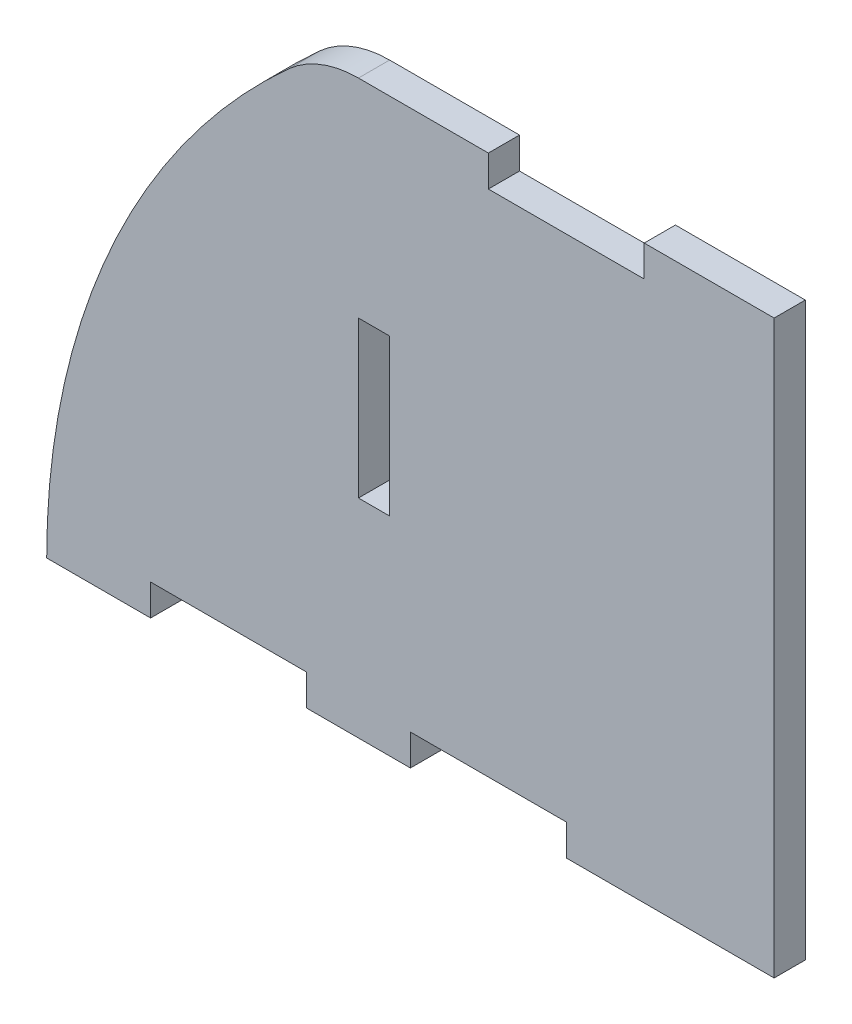
SolidWorks part; units mm, degrees
material "ABS PC"
ref_plane "Front Plane" through (0, 0, 0) normal (0, 0, 1) x (1, 0, 0)
ref_plane "Top Plane" through (0, 0, 0) normal (0, 1, 0) x (1, 0, 0)
ref_plane "Right Plane" through (0, 0, 0) normal (1, 0, 0) x (0, 0, -1)
sketch "Sketch1" plane through (0, 0, 0) normal (0, 0, 1) x (1, 0, 0)
  line L0 (0, 0) -> (0, 55)
  line L1 (0, 55) -> (-40, 55)
  line L2 (-40, 55) -> (-70, 55) construction
  line L3 (-70, 55) -> (-70, 0) construction
  line L4 (-70, 0) -> (0, 0)
  arc A0 (-46.701, 52.4227) -> (-70, 0) centre (0.625, 0) ccw
  arc A1 (-40, 55) -> (-46.701, 52.4227) centre (-40, 45) ccw
  dimension "D4" = 10
  dimension "D1" = 55
  dimension "D2" = 40
  dimension "D3" = 70
extrude "Boss-Extrude1" add sketch "Sketch1" along normal blind 3
sketch "Sketch2" plane through (0, 0, 3) normal (0, 0, 1) x (1, 0, 0)
  line L0 (0, 55) -> (-40, 55) construction
  line L1 (-27.5, 55) -> (-12.5, 55)
  line L2 (-27.5, 55) -> (-27.5, 52)
  line L3 (-27.5, 52) -> (-12.5, 52)
  line L4 (-12.5, 55) -> (-12.5, 52)
  line L5 (-70, 0) -> (0, 0) construction
  line L6 (-35, 0) -> (-20, 0)
  line L7 (-35, 0) -> (-35, 3)
  line L8 (-35, 3) -> (-20, 3)
  line L9 (-20, 0) -> (-20, 3)
  line L10 (-37, 27.5) -> (0, 27.5) construction
  line L11 (-60, 0) -> (-45, 0)
  line L12 (-60, 0) -> (-60, 3)
  line L13 (-60, 3) -> (-45, 3)
  line L14 (-45, 0) -> (-45, 3)
  line L15 (-40, 35) -> (-37, 35)
  line L16 (-40, 35) -> (-40, 20)
  line L17 (-40, 20) -> (-37, 20)
  line L18 (-37, 35) -> (-37, 20)
  line L19 (0, 0) -> (0, 55) construction
  line L20 (-40, 35) -> (-40, 55) construction
  line L21 (-40, 52) -> (-27.5, 52) construction
  line L22 (-12.5, 52) -> (0, 52) construction
  line L23 (0, 0) -> (-20, 0) construction
  line L24 (-70, 0) -> (-60, 0) construction
  dimension "D1" = 3
  dimension "D2" = 15
  dimension "D3" = 20
  dimension "D4" = 10
  dimension "D5" = 10
extrude "Cut-Extrude1" cut sketch "Sketch2" against normal through all
